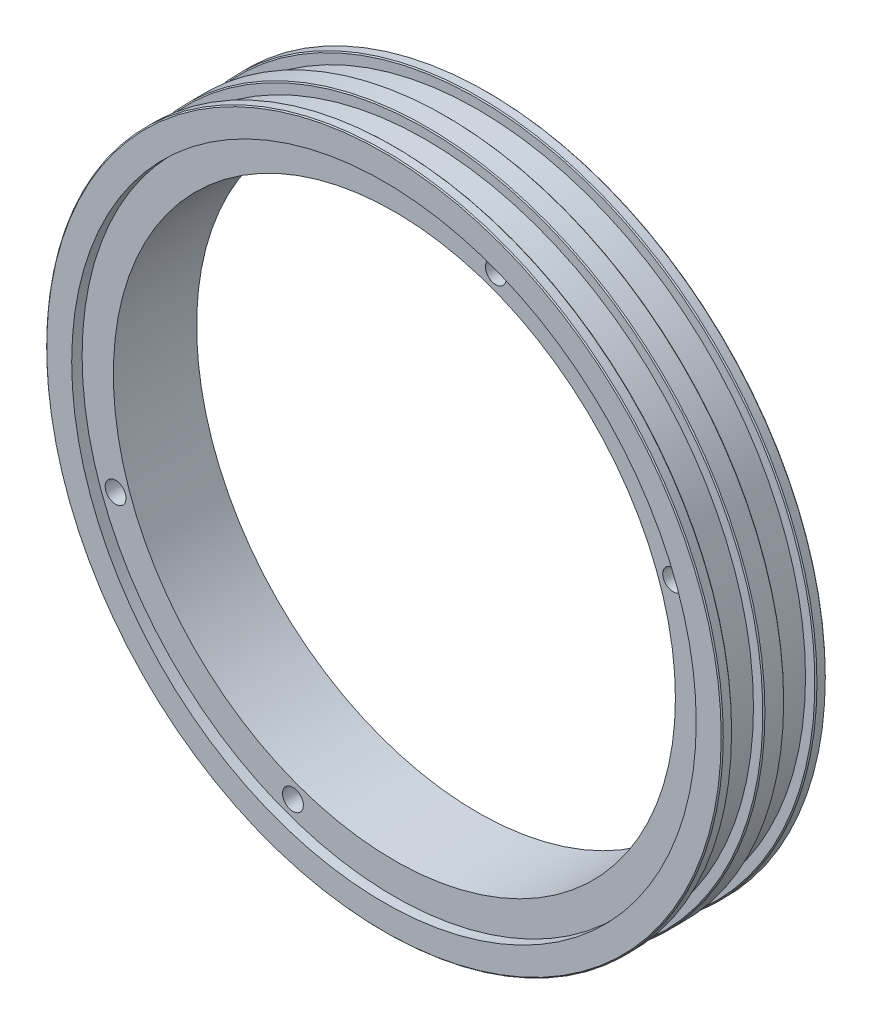
SolidWorks part; units mm, degrees
ref_plane "Front Plane" through (0, 0, 0) normal (0, 0, 1) x (1, 0, 0)
ref_plane "Top Plane" through (0, 0, 0) normal (0, 1, 0) x (1, 0, 0)
ref_plane "Right Plane" through (0, 0, 0) normal (1, 0, 0) x (0, 0, -1)
sketch "Sketch1" plane through (0, 0, 0) normal (0, 0, 1) x (1, 0, 0)
  circle A0 centre (0, 0) radius 82.55
extrude "Boss-Extrude1" add sketch "Sketch1" along normal blind 25.4
sketch "Sketch2" plane through (0, 0, 0) normal (0, 0, 1) x (1, 0, 0)
  circle A0 centre (0, 0) radius 68.58
extrude "Cut-Extrude1" cut sketch "Sketch2" along normal blind 25.4
sketch "Sketch3" plane through (0, 0, 0) normal (0, 0, 1) x (1, 0, 0)
  circle A0 centre (0, 0) radius 76.2
extrude "Cut-Extrude2" cut sketch "Sketch3" along normal blind 2.54
sketch "Sketch4" plane through (0, 0, 25.4) normal (0, 0, 1) x (1, 0, 0)
  circle A0 centre (0, 0) radius 76.2
extrude "Cut-Extrude3" cut sketch "Sketch4" against normal blind 2.54
sketch "Sketch5" plane through (0, 0, 0) normal (0, 1, 0) x (1, 0, 0)
  line L0 (82.55, 0) -> (-82.55, 0) construction
  line L1 (-82.55, 0) -> (-82.55, -25.4) construction
  line L2 (-82.55, -2.54) -> (-80.01, -2.54)
  line L3 (0, 0) -> (0, -25.4) construction
  line L4 (-82.55, -25.4) -> (82.55, -25.4) construction
  line L5 (0, -12.7) -> (-82.55, -12.7) construction
  line L6 (-82.55, -22.86) -> (-82.55, -15.24)
  line L7 (-82.55, -10.16) -> (-80.01, -10.16)
  line L8 (-80.01, -10.16) -> (-80.01, -2.54)
  line L9 (-82.55, -2.54) -> (-82.55, -10.16)
  line L10 (-80.01, -15.24) -> (-80.01, -22.86)
  line L11 (-82.55, -15.24) -> (-80.01, -15.24)
  line L12 (-82.55, -22.86) -> (-80.01, -22.86)
  dimension "D1" = 2.54
  dimension "D2" = 7.62
revolve "Cut-Revolve1" cut sketch "Sketch5" angle 360 about L3
chamfer "Chamfer1" distance 0.254 angle 45 1 edges at (-82.55, 0, 10.16)
chamfer "Chamfer2" distance 0.254 angle 45 1 edges at (-82.55, 0, 15.24)
chamfer "Chamfer3" distance 0.254 angle 45 1 edges at (-82.55, 0, 2.54)
chamfer "Chamfer4" distance 0.254 angle 45 1 edges at (-82.55, 0, 22.86)
chamfer "Chamfer5" distance 0.254 angle 45 1 edges at (82.55, 0, 0)
chamfer "Chamfer6" distance 0.254 angle 45 1 edges at (82.55, 0, 25.4)
sketch "Sketch6" plane through (0, 0, 0) normal (0, 0, 1) x (1, 0, 0)
  line L0 (0, 0) -> (0, 76.2) construction
  line L1 (0, 0) -> (68.58, 0) construction
  line L2 (0, 0) -> (51.1875, 51.1875) construction
  line L3 (0, 0) -> (-51.1875, 51.1875) construction
  circle A1 centre (0, 0) radius 76.2 construction
  circle A2 centre (0, 0) radius 68.58 construction
  circle A5 centre (68.0243, 24.7588) radius 2.54
  circle A6 centre (-68.0243, -24.7588) radius 2.54
  circle A7 centre (24.7588, 68.0243) radius 2.54
  circle A8 centre (-24.7588, -68.0243) radius 2.54
  point P24 (0, 0)
  point P29 (0, 0)
extrude "Cut-Extrude4" cut sketch "Sketch6" along normal through all
